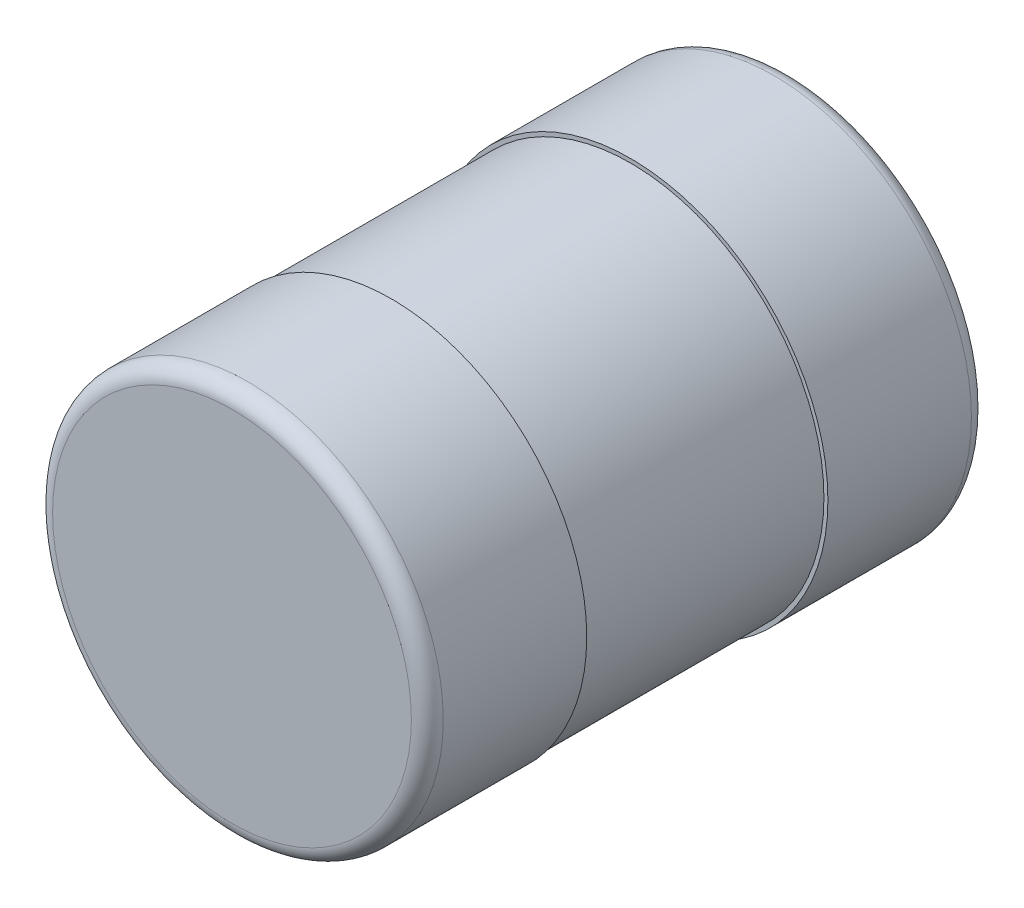
SolidWorks part; units mm, degrees
ref_plane "정면" through (0, 0, 0) normal (0, 0, 1) x (1, 0, 0)
ref_plane "윗면" through (0, 0, 0) normal (0, 1, 0) x (1, 0, 0)
ref_plane "우측면" through (0, 0, 0) normal (1, 0, 0) x (0, 0, -1)
sketch "스케치1" plane through (0, 0, 0) normal (0, 0, 1) x (1, 0, 0)
  circle A0 centre (0, 0) radius 2.475
  dimension "D1" = 4.95
extrude "보스-돌출1" add sketch "스케치1" along normal blind 2
sketch "스케치2" plane through (0, 0, 2) normal (0, 0, 1) x (1, 0, 0)
  circle A0 centre (0, 0) radius 2.425
  dimension "D1" = 4.85
extrude "보스-돌출2" add sketch "스케치2" along normal blind 3
sketch "스케치3" plane through (0, 0, 5) normal (0, 0, 1) x (1, 0, 0)
  circle A0 centre (0, 0) radius 2.45
  dimension "D1" = 4.9
extrude "보스-돌출3" add sketch "스케치3" along normal blind 2
fillet "필렛1" radius 0.2 2 edges at (2.45, 0, 7) (2.475, 0, 0)
